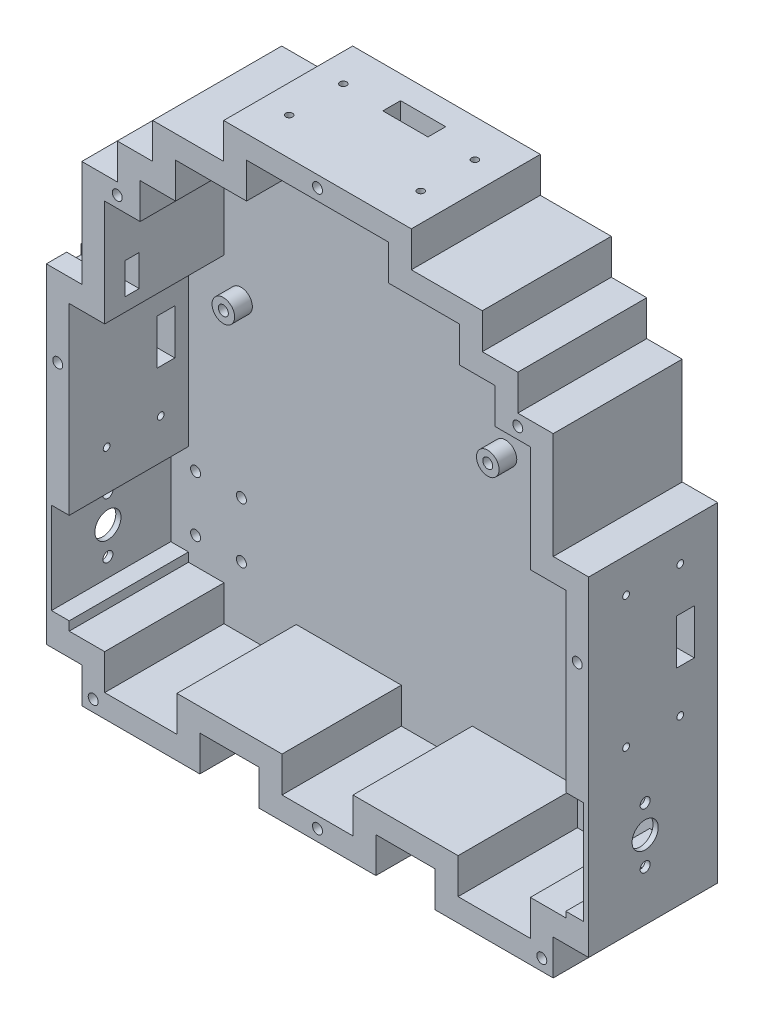
SolidWorks part; units mm, degrees
ref_plane "Alzado" through (0, 0, 0) normal (0, 0, 1) x (1, 0, 0)
ref_plane "Planta" through (0, 0, 0) normal (0, 1, 0) x (1, 0, 0)
ref_plane "Vista lateral" through (0, 0, 0) normal (1, 0, 0) x (0, 0, -1)
sketch "PacmanSilueta" plane through (0, 0, 0) normal (0, 0, 1) x (1, 0, 0)
  line L0 (82, -27) -> (82, -5) construction
  line L3 (-61, -104) -> (-39, -104)
  line L5 (-61, -104) -> (-61, -27) construction
  line L6 (-50, -104) -> (-50, 6) construction
  line L7 (-39, -104) -> (-39, 17) construction
  line L8 (-28, -93) -> (-28, 28) construction
  line L9 (-17, -93) -> (-17, 28) construction
  line L10 (-6, -104) -> (-6, 39) construction
  line L11 (5, -104) -> (5, 28) construction
  line L12 (16, -104) -> (16, 28) construction
  line L13 (27, -93) -> (27, 28) construction
  line L14 (38, -93) -> (38, 28) construction
  line L15 (49, -104) -> (49, 17) construction
  line L16 (60, -104) -> (60, 6) construction
  line L17 (71, -104) -> (71, -27) construction
  line L18 (82, -93) -> (82, -27) construction
  line L19 (49, -104) -> (71, -104)
  line L20 (-72, -93) -> (-28, -93) construction
  line L21 (-72, -82) -> (82, -82) construction
  line L22 (-72, -71) -> (82, -71) construction
  line L23 (-72, -60) -> (82, -60) construction
  line L24 (-72, -49) -> (82, -49) construction
  line L25 (-72, -38) -> (82, -38) construction
  line L26 (-61, -27) -> (82, -27) construction
  line L27 (-61, -16) -> (71, -16) construction
  line L28 (-61, -5) -> (60, -5) construction
  line L29 (-50, 6) -> (60, 6) construction
  line L30 (-39, 17) -> (49, 17) construction
  line L31 (-17, 28) -> (27, 28) construction
  line L33 (-61, -5) -> (-61, 6) construction
  line L35 (-72, -93) -> (-61, -93)
  line L36 (-61, -93) -> (-61, -104)
  line L37 (-61, -104) -> (-39, -104)
  line L38 (-39, -104) -> (-39, -93)
  line L39 (-39, -93) -> (-28, -93)
  line L40 (-28, -93) -> (-28, -82)
  line L41 (-28, -82) -> (-17, -82)
  line L42 (-17, -82) -> (-17, -93)
  line L43 (-17, -93) -> (-6, -93)
  line L44 (-6, -93) -> (-6, -104)
  line L45 (-6, -104) -> (16, -104)
  line L46 (16, -104) -> (16, -93)
  line L47 (16, -93) -> (27, -93)
  line L48 (27, -93) -> (27, -82)
  line L49 (27, -82) -> (38, -82)
  line L50 (38, -82) -> (38, -93)
  line L51 (38, -93) -> (49, -93)
  line L52 (49, -93) -> (49, -104)
  line L53 (49, -104) -> (71, -104)
  line L54 (71, -104) -> (71, -93)
  line L55 (71, -93) -> (82, -93)
  line L56 (82, -93) -> (82, -27)
  line L57 (38, -93) -> (82, -93) construction
  line L58 (-6, -104) -> (16, -104)
  line L59 (-17, -93) -> (27, -93) construction
  line L60 (82, -5) -> (71, -5) construction
  line L61 (71, -5) -> (71, 6) construction
  line L62 (-72, -93) -> (-79.1, -93)
  line L63 (93, -60) -> (93, -27) construction
  line L64 (-72, -27) -> (-72, -5)
  line L65 (-72, -5) -> (-61, -5)
  line L66 (-61, -5) -> (-61, 28)
  line L67 (-61, 28) -> (-50, 28)
  line L68 (-50, 28) -> (-50, 39)
  line L69 (-50, 39) -> (-39, 39)
  line L70 (-39, 39) -> (-39, 50)
  line L71 (-39, 50) -> (-17, 50)
  line L72 (-17, 50) -> (-17, 61)
  line L73 (-17, 61) -> (27, 61)
  line L74 (27, 61) -> (27, 50)
  line L75 (27, 50) -> (49, 50)
  line L76 (49, 50) -> (49, 39)
  line L77 (49, 39) -> (60, 39)
  line L78 (-79.1, -93) -> (-79.1, 2.1)
  line L79 (-72, -27) -> (-72, -93)
  line L83 (-72, 50) -> (-61, 50) construction
  line L84 (-72, 61) -> (-61, 61) construction
  line L88 (71, 6) -> (71, 28) construction
  line L89 (71, 28) -> (60, 28) construction
  line L90 (60, 28) -> (60, 17) construction
  line L92 (49, 28) -> (49, 39) construction
  line L93 (49, 39) -> (60, 39) construction
  line L94 (60, 39) -> (60, 28) construction
  line L95 (27, 39) -> (27, 50) construction
  line L96 (27, 50) -> (49, 50) construction
  line L97 (49, 50) -> (49, 39) construction
  line L99 (27, 50) -> (27, 61) construction
  line L100 (27, 61) -> (-17, 61) construction
  line L101 (-17, 61) -> (-17, 39) construction
  line L103 (-17, 50) -> (-39, 50) construction
  line L104 (-39, 50) -> (-39, 28) construction
  line L106 (-39, 39) -> (-50, 39) construction
  line L107 (-50, 39) -> (-50, 17) construction
  line L109 (-50, 28) -> (-61, 28) construction
  line L110 (-61, 28) -> (-61, 6) construction
  line L112 (-61, -5) -> (-72, -5) construction
  line L113 (-72, -5) -> (-72, -27) construction
  line L114 (60, 39) -> (60, 28)
  line L115 (16, 39) -> (27, 39) construction
  line L116 (60, 28) -> (71, 28)
  line L117 (71, 28) -> (71, -5)
  line L118 (71, -5) -> (82, -5)
  line L119 (82, -5) -> (82, -27)
  line L120 (-72, -5) -> (-79.1, -5) construction
  line L121 (-61, 2.1) -> (-68.1, 2.1) construction
  line L122 (-79.1, 2.1) -> (-68.1, 2.1)
  line L123 (-68.1, 2.1) -> (-68.1, 35.1)
  line L124 (-61, 28) -> (-61, 39) construction
  line L125 (-50, 39) -> (-50, 46.1) construction
  line L126 (-39, 50) -> (-39, 57.1) construction
  line L127 (-17, 61) -> (-17, 68.1) construction
  line L128 (-61, 28) -> (-61, 35.1) construction
  line L129 (-50, 35.1) -> (-57.1, 35.1) construction
  line L130 (-39, 44.5) -> (-46.1, 44.5) construction
  line L131 (-17, 57.1) -> (-24.1, 57.1) construction
  line L132 (-68.1, 35.1) -> (-57.1, 35.1)
  line L133 (-57.1, 35.1) -> (-57.1, 46.1)
  line L134 (-57.1, 46.1) -> (-46.1, 46.1)
  line L135 (-46.1, 46.1) -> (-46.1, 57.1)
  line L136 (-46.1, 57.1) -> (-24.1, 57.1)
  line L137 (-24.1, 57.1) -> (-24.1, 68.1)
  line L138 (5, 79.3678) -> (5, -133.8211) construction
  line L139 (-24.1, 68.1) -> (34.1, 68.1)
  line L140 (-63.847, -93) -> (-63.847, -100.1) construction
  line L141 (-55.3933, -104) -> (-55.3933, -111.1) construction
  line L142 (-61, -104) -> (-68.1, -104) construction
  line L143 (-79.1, -93) -> (-79.1, -100.1)
  line L144 (-79.1, -100.1) -> (-68.1, -100.1)
  line L145 (-68.1, -100.1) -> (-68.1, -111.1)
  line L146 (-39, -96.7914) -> (-31.9, -96.7914) construction
  line L147 (-68.1, -111.1) -> (-31.4864, -111.1)
  line L148 (-37.2832, -93) -> (-37.2832, -100.1) construction
  line L149 (-6, -100.1) -> (-13.1, -100.1) construction
  line L150 (-31.4864, -100.1) -> (-31.4864, -111.1)
  line L151 (-31.4864, -100.1) -> (-13.1, -100.1)
  line L152 (-13.1, -100.1) -> (-13.1, -111.1)
  line L153 (-13.1, -111.1) -> (23.1, -111.1)
  line L154 (34.1, 57.1) -> (34.1, 68.1)
  line L155 (56.1, 57.1) -> (34.1, 57.1)
  line L156 (56.1, 46.1) -> (56.1, 57.1)
  line L157 (67.1, 46.1) -> (56.1, 46.1)
  line L158 (67.1, 35.1) -> (67.1, 46.1)
  line L159 (78.1, 35.1) -> (67.1, 35.1)
  line L160 (89.1, 2.1) -> (78.1, 2.1)
  line L161 (78.1, 2.1) -> (78.1, 35.1)
  line L162 (89.1, -93) -> (89.1, -100.1)
  line L163 (89.1, -93) -> (89.1, 2.1)
  line L164 (89.1, -100.1) -> (78.1, -100.1)
  line L165 (78.1, -100.1) -> (78.1, -111.1)
  line L166 (78.1, -111.1) -> (41.4864, -111.1)
  line L167 (41.4864, -100.1) -> (41.4864, -111.1)
  line L168 (41.4864, -100.1) -> (23.1, -100.1)
  line L169 (23.1, -100.1) -> (23.1, -111.1)
  point P0 (0, 0)
  point P133 (5, 68.1)
  point P148 (5, -111.1)
  dimension "D1" = 22
  dimension "D2" = 22
  dimension "D3" = 22
  dimension "D4" = 7.1
  dimension "D7" = 7.1
  dimension "D8" = 7.1
  dimension "D9" = 7.1
  dimension "D10" = 7.1
  dimension "D11" = 7.1
  dimension "D12" = 7.1
  dimension "D13" = 7.1
  dimension "D14" = 7.1
  dimension "D15" = 7.1
  dimension "D16" = 7.1
  dimension "D17" = 7.1
  dimension "D18" = 7.1
  dimension "D19" = 7.1
  dimension "D20" = 7.1
  dimension "D21" = 7.1
  dimension "D6" = 15
  dimension "D5" = 15
extrude "Saliente-Extruir3" add sketch "PacmanSilueta" against normal blind 3
sketch "Croquis3" plane through (0, 0, 0) normal (0, 0, 1) x (1, 0, 0)
  line L102 (-72, -5) -> (-72, -93)
  line L103 (-72, -93) -> (-61, -93)
  line L104 (-61, -93) -> (-61, -104)
  line L105 (-61, -104) -> (-38.5864, -104)
  line L106 (-38.5864, -104) -> (-38.5864, -93)
  line L107 (-38.5864, -93) -> (-6, -93)
  line L108 (-6, -93) -> (-6, -104)
  line L109 (-6, -104) -> (16, -104)
  line L110 (16, -104) -> (16, -93)
  line L111 (16, -93) -> (48.5864, -93)
  line L112 (48.5864, -93) -> (48.5864, -104)
  line L113 (48.5864, -104) -> (71, -104)
  line L114 (71, -104) -> (71, -93)
  line L115 (71, -93) -> (82, -93)
  line L116 (82, -93) -> (82, -5)
  line L117 (82, -5) -> (71, -5)
  line L118 (71, -5) -> (71, 28)
  line L119 (71, 28) -> (60, 28)
  line L120 (60, 28) -> (60, 39)
  line L121 (60, 39) -> (49, 39)
  line L122 (49, 39) -> (49, 50)
  line L123 (49, 50) -> (27, 50)
  line L124 (27, 50) -> (27, 61)
  line L125 (27, 61) -> (-17, 61)
  line L126 (-17, 61) -> (-17, 50)
  line L127 (-17, 50) -> (-39, 50)
  line L128 (-39, 50) -> (-39, 39)
  line L129 (-39, 39) -> (-50, 39)
  line L130 (-50, 39) -> (-50, 28)
  line L131 (-50, 28) -> (-61, 28)
  line L132 (-61, 28) -> (-61, -5)
  line L133 (-61, -5) -> (-72, -5)
  line L134 (-72, -5) -> (-72, -93)
  line L135 (-72, -93) -> (-61, -93)
  line L136 (-61, -93) -> (-61, -104)
  line L137 (-61, -104) -> (-38.5864, -104)
  line L138 (-38.5864, -104) -> (-38.5864, -93)
  line L139 (-38.5864, -93) -> (-6, -93)
  line L140 (-6, -93) -> (-6, -104)
  line L141 (-6, -104) -> (16, -104)
  line L142 (16, -104) -> (16, -93)
  line L143 (16, -93) -> (48.5864, -93)
  line L144 (48.5864, -93) -> (48.5864, -104)
  line L145 (48.5864, -104) -> (71, -104)
  line L146 (71, -104) -> (71, -93)
  line L147 (71, -93) -> (82, -93)
  line L148 (82, -93) -> (82, -5)
  line L149 (82, -5) -> (71, -5)
  line L150 (71, -5) -> (71, 28)
  line L151 (71, 28) -> (60, 28)
  line L152 (60, 28) -> (60, 39)
  line L153 (60, 39) -> (49, 39)
  line L154 (49, 39) -> (49, 50)
  line L155 (49, 50) -> (27, 50)
  line L156 (27, 50) -> (27, 61)
  line L157 (27, 61) -> (-17, 61)
  line L158 (-17, 61) -> (-17, 50)
  line L159 (-17, 50) -> (-39, 50)
  line L160 (-39, 50) -> (-39, 39)
  line L161 (-39, 39) -> (-50, 39)
  line L162 (-50, 39) -> (-50, 28)
  line L163 (-50, 28) -> (-61, 28)
  line L164 (-61, 28) -> (-61, -5)
  line L165 (-61, -5) -> (-72, -5)
  dimension "D1" = 7.1
extrude "Saliente-Extruir4" add sketch "Croquis3" along normal blind 37
sketch "Croquis15" plane through (0, 68.1, 0) normal (0, 1, 0) x (1, 0, 0)
  line L0 (5, -37) -> (5, 9.6644) construction
  line L1 (34.1, -37) -> (-24.1, -37) construction
  line L2 (34.1, -17) -> (-27.6172, -17) construction
  line L3 (34.1, 3) -> (34.1, -37) construction
  line L4 (-17, -7) -> (-17, -8.6) construction
  line L5 (27, -27) -> (-17, -27)
  line L6 (27, -27) -> (27, -7)
  line L7 (27, -7) -> (-17, -7)
  line L8 (-17, -27) -> (-17, -7)
  line L9 (27, -27) -> (-17, -7) construction
  line L10 (27, -7) -> (-17, -27) construction
  line L11 (-17, -8.6) -> (-15.4, -8.6) construction
  line L13 (12, -9.75) -> (-2, -9.75)
  line L14 (12, -9.75) -> (12, -4.25)
  line L15 (12, -4.25) -> (-2, -4.25)
  line L16 (-2, -9.75) -> (-2, -4.25)
  line L17 (12, -9.75) -> (-2, -4.25) construction
  line L18 (12, -4.25) -> (-2, -9.75) construction
  circle A0 centre (-15.4, -8.6) radius 1.05
  circle A1 centre (-15.4, -25.4) radius 1.05
  circle A2 centre (25.4, -8.6) radius 1.05
  circle A3 centre (25.4, -25.4) radius 1.05
  point P8 (5, -17)
  point P22 (5, -7)
  dimension "D5" = 2.1
  dimension "D1" = 44
  dimension "D2" = 20
  dimension "D3" = 1.6
  dimension "D4" = 1.6
  dimension "D6" = 14
  dimension "D7" = 5.5
extrude "Cortar-Extruir6" cut sketch "Croquis15" against normal blind 9 contours A3 | A2 | L16 L13 L14 L7 | A1 | A0
sketch "Croquis17" plane through (-79.1, 0, 0) normal (-1, 0, 0) x (0, 0, 1)
  line L0 (17, 2.1) -> (17, -105.6496) construction
  line L1 (-3, 2.1) -> (37, 2.1) construction
  line L2 (-3, 2.1) -> (37, 2.1) construction
  line L3 (27, -7) -> (7, -7)
  line L4 (27, -7) -> (27, -51)
  line L5 (27, -51) -> (7, -51)
  line L6 (7, -7) -> (7, -51)
  line L7 (27, -7) -> (7, -51) construction
  line L8 (27, -51) -> (7, -7) construction
  line L9 (7, -51) -> (8.6, -51) construction
  line L10 (8.6, -51) -> (8.6, -49.4) construction
  line L11 (27, -29) -> (5.4677, -29) construction
  line L12 (17, -99.9582) -> (17, -93.7345) construction
  line L13 (9.75, -22) -> (4.25, -22)
  line L14 (9.75, -22) -> (9.75, -36)
  line L15 (9.75, -36) -> (4.25, -36)
  line L16 (4.25, -22) -> (4.25, -36)
  line L17 (9.75, -22) -> (4.25, -36) construction
  line L18 (9.75, -36) -> (4.25, -22) construction
  circle A0 centre (8.6, -49.4) radius 1.05
  circle A1 centre (25.4, -49.4) radius 1.05
  circle A2 centre (8.6, -8.6) radius 1.05
  circle A3 centre (25.4, -8.6) radius 1.05
  point P4 (17, -29)
  point P22 (7, -29)
  dimension "D6" = 2.1
  dimension "D1" = 44
  dimension "D2" = 20
  dimension "D3" = 9.1
  dimension "D4" = 1.6
  dimension "D5" = 1.6
  dimension "D7" = 14
  dimension "D8" = 5.5
extrude "Cortar-Extruir7" cut sketch "Croquis17" against normal through all contours L15 L14 L13 L6 | L13 L16 L15 L6 | A3 | A2 | A1 | A0
sketch "Croquis18" plane through (-72, 0, 0) normal (1, 0, 0) x (0, 0, -1)
  line L0 (0, -83.9821) -> (-19.5, -83.9821) construction
  line L1 (0, -5) -> (0, -93) construction
  line L2 (0, -89.9037) -> (-35.8183, -89.9037) construction
  line L3 (-35.8183, -89.9037) -> (-35.8183, -61.9037) construction
  line L4 (-35.8183, -61.9037) -> (1.1103, -61.9037) construction
  line L5 (-35.8183, -75.9037) -> (4.9689, -75.9037) construction
  line L6 (-19.5, -75.9037) -> (-19.5, -67.3037) construction
  line L7 (-17.95, -67.3037) -> (3, -67.3037) construction
  line L8 (3, 2.1) -> (3, -100.1) construction
  line L9 (-17.95, -84.5037) -> (3, -84.5037) construction
  circle A0 centre (-19.5, -75.9037) radius 4.05
  circle A1 centre (-19.5, -67.3037) radius 1.55
  circle A2 centre (-19.5, -84.5037) radius 1.55
  dimension "D3" = 8.1
  dimension "D5" = 3.1
  dimension "D1" = 19.5
  dimension "D2" = 28
  dimension "D4" = 8.6
extrude "Cortar-Extruir8" cut sketch "Croquis18" against normal through all and the other way through all
sketch "Croquis20" plane through (-72, 0, 0) normal (1, 0, 0) x (0, 0, -1)
  line L0 (0, -75.9037) -> (0, -64.5552)
  line L1 (0, -5) -> (0, -93) construction
  line L2 (0, -61.907) -> (-39.6382, -61.907)
  line L3 (-39.6382, -61.907) -> (-39.6382, -90.2223)
  line L4 (-39.6382, -90.2223) -> (0, -90.2223)
  circle M3 centre (-19.5, -84.5037) radius 1.55
  circle M4 centre (-19.5, -67.3037) radius 1.55
  circle M5 centre (-19.5, -75.9037) radius 4.05
  line M9 (0, -93) -> (0, -5)
extrude "Cortar-Extruir9" cut sketch "Croquis20" against normal blind 5.5 contours L3 L4 L2 M9 M3 M5 M4
sketch "Croquis21" plane through (82, 0, 0) normal (-1, 0, 0) x (0, 0, 1)
  line L0 (0, -59.3237) -> (38.7031, -59.3237)
  line L1 (0, -93) -> (0, -5) construction
  line L2 (38.7031, -59.3237) -> (38.7031, -91.2263)
  line L3 (38.7031, -91.2263) -> (0, -91.2263)
  circle M4 centre (19.5, -84.5037) radius 1.55
  circle M5 centre (19.5, -67.3037) radius 1.55
  circle M6 centre (19.5, -75.9037) radius 4.05
  line M10 (0, -5) -> (0, -93)
extrude "Cortar-Extruir11" cut sketch "Croquis21" against normal blind 5.5 contours L3 L2 L0 M10 M5 M6 M4
sketch "Croquis24" plane through (0, 0, 0) normal (0, 0, 1) x (1, 0, 0)
  line L0 (-77.5, -76.0647) -> (-77.5, -67.4647) construction
  line L1 (-77.5, -90.2223) -> (-77.5, -61.907) construction
  line L2 (-77.5, -67.4647) -> (-55.1447, -67.4647) construction
  line L3 (-77.5, -76.0647) -> (-77.5, -84.6647) construction
  line L4 (-77.5, -84.6647) -> (-51.118, -84.6647) construction
  line L5 (-77.5, -76.0647) -> (-50.5062, -76.0647) construction
  line L6 (5, -104) -> (5, 3.2164) construction
  line L7 (-6, -104) -> (16, -104) construction
  line L8 (-61, 11.5) -> (-57.7057, 11.5) construction
  line L9 (-61, 28) -> (-61, -5) construction
  line L10 (-57.7057, 11.5) -> (-57.7057, 24.5049)
  line L11 (-57.7057, 24.5049) -> (-9.1339, 24.5049)
  line L12 (-57.7057, 11.5) -> (-57.7057, -16.4951)
  line L13 (-57.7057, -16.4951) -> (28.2943, -16.4951)
  line L14 (28.2943, -16.4951) -> (28.2943, 24.5049)
  line L15 (28.2943, 24.5049) -> (-9.1339, 24.5049)
  line L16 (-57.7057, 24.5049) -> (-55.7057, 24.5049) construction
  line L17 (-55.7057, 24.5049) -> (-55.7057, 22.5049) construction
  line L18 (28.2943, 4.0049) -> (-57.7057, 4.0049) construction
  line L19 (-14.7057, -16.4951) -> (-14.7057, 24.5049) construction
  circle A0 centre (-69.8, -67.4647) radius 1.55
  circle A1 centre (-55.6, -67.4647) radius 1.55
  circle A2 centre (-55.6, -84.6647) radius 1.55
  circle A3 centre (-69.8, -84.6647) radius 1.55
  circle A4 centre (79.8, -84.6647) radius 1.55
  circle A5 centre (65.6, -84.6647) radius 1.55
  circle A6 centre (65.6, -67.4647) radius 1.55
  circle A7 centre (79.8, -67.4647) radius 1.55
  circle A8 centre (-55.7057, 22.5049) radius 1.55
  circle A9 centre (26.2943, 22.5049) radius 1.55
  circle A10 centre (26.2943, -14.4951) radius 1.55
  circle A11 centre (-55.7057, -14.4951) radius 1.55
  point P50 (0, 0)
  point P51 (0, 0)
  dimension "D4" = 3.1
  dimension "D5" = 3.1
  dimension "D11" = 3.1
  dimension "D1" = 8.6
  dimension "D2" = 7.7
  dimension "D3" = 14.2
  dimension "D6" = 8.6
  dimension "D7" = 41
  dimension "D8" = 86
  dimension "D9" = 2
  dimension "D10" = 2
extrude "Cortar-Extruir12" cut sketch "Croquis24" against normal blind 5.5 contours A9 | A11 | A6 | A10 | A8 | A0 | A1 | A2 | A3 | A7 | A4 | A5
sketch "Croquis25" plane through (0, 0, 0) normal (0, 0, 1) x (1, 0, 0)
  line L0 (-55.7057, 22.5049) -> (-55.7057, -14.4951) construction
  line L1 (-55.7057, 4.0049) -> (-43.5873, 4.0049) construction
  line L2 (-55.7057, 22.5049) -> (-55.7057, 28) construction
  line L3 (-50, 28) -> (-61, 28) construction
  circle A0 centre (-55.7057, -14.4951) radius 3.5
  circle A1 centre (-55.7057, 22.5049) radius 3.5
  circle A2 centre (26.2943, 22.5049) radius 3.5
  circle A3 centre (26.2943, -14.4951) radius 3.5
  circle A4 centre (-55.7057, 22.5049) radius 1.55
  circle A5 centre (-55.7057, -14.4951) radius 1.55
  circle A6 centre (26.2943, -14.4951) radius 1.55
  circle A7 centre (26.2943, 22.5049) radius 1.55
  dimension "D1" = 7
  dimension "D2" = 7
  dimension "D3" = 7
  dimension "D4" = 7
extrude "Saliente-Extruir5" add sketch "Croquis25" along normal blind 5.5
sketch "Croquis27" plane through (-61, 0, 0) normal (1, 0, 0) x (0, 0, -1)
  line L0 (-37, 28) -> (-37, 4) construction
  line L1 (-37, 28) -> (-37, -5) construction
  line L2 (0, 4) -> (-28.5, 4) construction
  line L3 (0, 28) -> (0, -5) construction
  line L5 (-30.7, 8.85) -> (-26.3, 8.85)
  line L6 (-30.7, 8.85) -> (-30.7, -0.85)
  line L7 (-30.7, -0.85) -> (-26.3, -0.85)
  line L8 (-26.3, 8.85) -> (-26.3, -0.85)
  line L9 (-30.7, 8.85) -> (-26.3, -0.85) construction
  line L10 (-30.7, -0.85) -> (-26.3, 8.85) construction
  dimension "D1" = 24
  dimension "D2" = 28.5
  dimension "D3" = 9.7
  dimension "D4" = 4.4
extrude "Cortar-Extruir13" cut sketch "Croquis27" against normal through all
sketch "Croquis28" plane through (0, 0, 37) normal (0, 0, 1) x (1, 0, 0)
  line L0 (5, -104) -> (5, -111.1) construction
  line L1 (-6, -104) -> (16, -104) construction
  line L2 (-13.1, -111.1) -> (23.1, -111.1) construction
  line L3 (5, -107.55) -> (23.1, -107.55) construction
  line L4 (23.1, -111.1) -> (23.1, -100.1) construction
  line L5 (5, 61) -> (5, 68.1) construction
  line L6 (27, 61) -> (-17, 61) construction
  line L7 (34.1, 68.1) -> (-24.1, 68.1) construction
  line L8 (89.1, -49) -> (82, -49) construction
  line L9 (89.1, -100.1) -> (89.1, 2.1) construction
  line L10 (82, -59.3237) -> (82, -5) construction
  line L11 (85.55, -49) -> (85.55, -9.5385) construction
  line L12 (85.55, -22.6707) -> (-85.0145, -22.6707) construction
  line L13 (-72, -33.4535) -> (-79.1, -33.4535) construction
  line L14 (-72, -5) -> (-72, -61.907) construction
  line L15 (-79.1, 2.1) -> (-79.1, -100.1) construction
  line L16 (-75.55, -33.4535) -> (-75.55, -22.6707) construction
  line L17 (-57.1, 35.1) -> (-57.1, 28) construction
  line L18 (-50, 28) -> (-61, 28) construction
  line L19 (67.1, 35.1) -> (67.1, 28) construction
  line L20 (71, 28) -> (60, 28) construction
  line L21 (-68.1, -111.1) -> (-61, -104) construction
  line L22 (71, -104) -> (78.1, -111.1) construction
  circle A0 centre (5, -107.55) radius 1.55
  circle A1 centre (5, 64.55) radius 1.55
  circle A2 centre (85.55, -22.6707) radius 1.55
  circle A3 centre (-75.55, -22.6707) radius 1.55
  circle A4 centre (-57.1, 31.55) radius 1.55
  circle A5 centre (67.1, 31.55) radius 1.55
  circle A6 centre (-64.55, -107.55) radius 1.55
  circle A7 centre (74.55, -107.55) radius 1.55
  dimension "D1" = 3.1
  dimension "D2" = 3.1
  dimension "D3" = 3.1
  dimension "D4" = 3.1
  dimension "D5" = 3.1
  dimension "D6" = 3.1
  dimension "D7" = 3.1
  dimension "D8" = 3.1
extrude "Cortar-Extruir14" cut sketch "Croquis28" against normal blind 5.5
